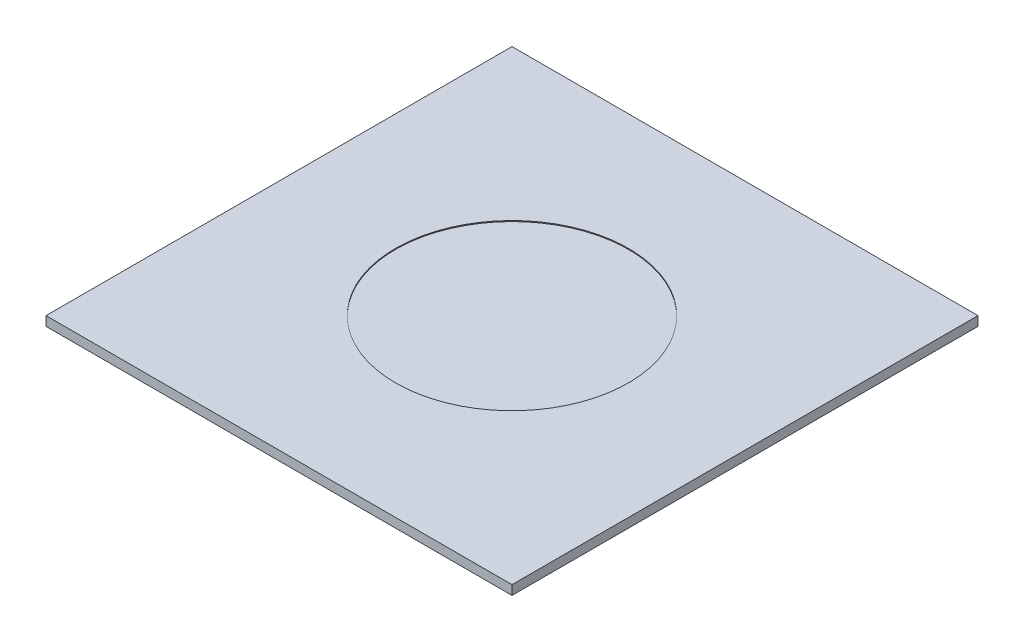
SolidWorks part; units mm, degrees
ref_plane "Front Plane" through (0, 0, 0) normal (0, 0, 1) x (1, 0, 0)
ref_plane "Top Plane" through (0, 0, 0) normal (0, 1, 0) x (1, 0, 0)
ref_plane "Right Plane" through (0, 0, 0) normal (1, 0, 0) x (0, 0, -1)
sketch "Sketch1" plane through (0, 0, 0) normal (0, 1, 0) x (1, 0, 0)
  line L1 (-250, 250) -> (250, 250)
  line L2 (-250, 250) -> (-250, -250)
  line L3 (-250, -250) -> (250, -250)
  line L4 (250, 250) -> (250, -250)
  line L5 (-250, 250) -> (250, -250) construction
  line L6 (-250, -250) -> (250, 250) construction
  point P0 (0, 0)
  dimension "D1" = 500
  dimension "D2" = 500
extrude "Boss-Extrude1" add sketch "Sketch1" along normal mid plane 10
sketch "Sketch2" plane through (0, 5, 0) normal (0, 1, 0) x (1, 0, 0)
  circle A0 centre (0, 0) radius 125
  dimension "D1" = 250
extrude "Cut-Extrude1" cut sketch "Sketch2" against normal blind 1
